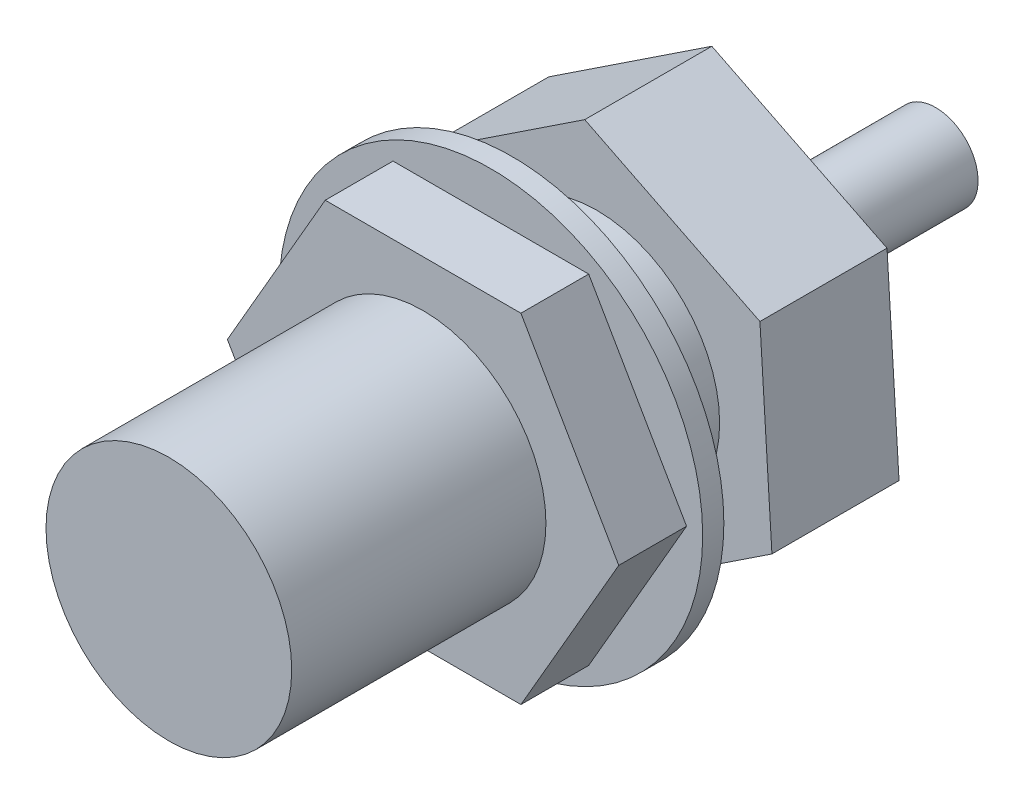
SolidWorks part; units mm, degrees
ref_plane "Front Plane" through (0, 0, 0) normal (0, 0, 1) x (1, 0, 0)
ref_plane "Top Plane" through (0, 0, 0) normal (0, 1, 0) x (1, 0, 0)
ref_plane "Right Plane" through (0, 0, 0) normal (1, 0, 0) x (0, 0, -1)
sketch "Sketch1" plane through (0, 0, 0) normal (0, 0, 1) x (1, 0, 0)
  circle A0 centre (0, 0) radius 2.9
  dimension "D1" = 5.8
extrude "Boss-Extrude1" add sketch "Sketch1" along normal mid plane 6
sketch "Sketch2" plane through (0, 0, -3) normal (0, 0, -1) x (-1, 0, 0)
  line L1 (4.6188, 0) -> (2.3094, 4)
  line L2 (2.3094, 4) -> (-2.3094, 4)
  line L3 (-2.3094, 4) -> (-4.6188, 0)
  line L4 (-4.6188, 0) -> (-2.3094, -4)
  line L5 (-2.3094, -4) -> (2.3094, -4)
  line L6 (2.3094, -4) -> (4.6188, 0)
  circle A0 centre (0, 0) radius 4 construction
  dimension "D1" = 8
extrude "Boss-Extrude2" add sketch "Sketch2" along normal blind 1.6
sketch "Sketch3" plane through (0, 0, -4.6) normal (0, 0, -1) x (-1, 0, 0)
  circle A0 centre (0, 0) radius 5
  dimension "D1" = 10
extrude "Boss-Extrude3" add sketch "Sketch3" along normal blind 0.5
sketch "Sketch4" plane through (0, 0, -5.1) normal (0, 0, -1) x (-1, 0, 0)
  circle A0 centre (0, 0) radius 2.9
extrude "Boss-Extrude4" add sketch "Sketch4" along normal blind 2
sketch "Sketch5" plane through (0, 0, -7.1) normal (0, 0, -1) x (-1, 0, 0)
  line L1 (4.1344, 2.0592) -> (0.2839, 4.6101)
  line L2 (0.2839, 4.6101) -> (-3.8505, 2.5509)
  line L3 (-3.8505, 2.5509) -> (-4.1344, -2.0592)
  line L4 (-4.1344, -2.0592) -> (-0.2839, -4.6101)
  line L5 (-0.2839, -4.6101) -> (3.8505, -2.5509)
  line L6 (3.8505, -2.5509) -> (4.1344, 2.0592)
  circle A0 centre (0, 0) radius 4 construction
  dimension "D1" = 8
extrude "Boss-Extrude5" add sketch "Sketch5" along normal blind 3
sketch "Sketch6" plane through (0, 0, -10.1) normal (0, 0, -1) x (-1, 0, 0)
  circle A0 centre (0, 0) radius 1
  dimension "D1" = 2
extrude "Boss-Extrude6" add sketch "Sketch6" along normal blind 5
